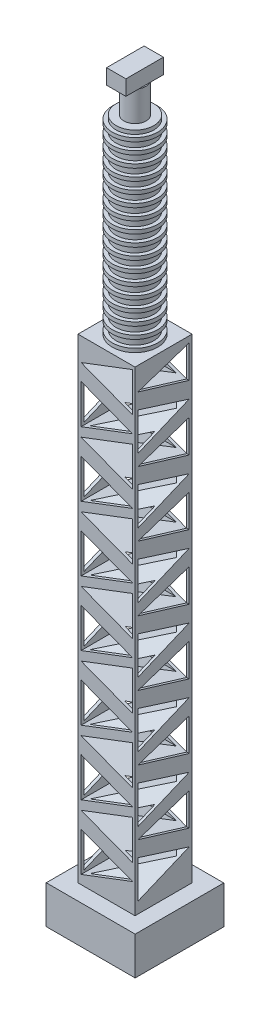
SolidWorks part; units mm, degrees
ref_plane "Alzado" through (0, 0, 0) normal (0, 0, 1) x (1, 0, 0)
ref_plane "Planta" through (0, 0, 0) normal (0, 1, 0) x (1, 0, 0)
ref_plane "Vista lateral" through (0, 0, 0) normal (1, 0, 0) x (0, 0, -1)
sketch "Croquis1" plane through (0, 0, 0) normal (0, 1, 0) x (1, 0, 0)
  line L1 (-150, 150) -> (150, 150)
  line L2 (-150, 150) -> (-150, -150)
  line L3 (-150, -150) -> (150, -150)
  line L4 (150, 150) -> (150, -150)
  line L5 (-150, 150) -> (150, -150) construction
  line L6 (-150, -150) -> (150, 150) construction
  point P0 (0, 0)
  dimension "D1" = 300
  dimension "D2" = 300
extrude "Saliente-Extruir1" add sketch "Croquis1" along normal blind 2500
sketch "Croquis2" plane through (0, 0, 0) normal (0, -1, 0) x (1, 0, 0)
  line L1 (234.0022, -233.0586) -> (-234.0022, -233.0586)
  line L2 (234.0022, -233.0586) -> (234.0022, 233.0586)
  line L3 (234.0022, 233.0586) -> (-234.0022, 233.0586)
  line L4 (-234.0022, -233.0586) -> (-234.0022, 233.0586)
  line L5 (234.0022, -233.0586) -> (-234.0022, 233.0586) construction
  line L6 (234.0022, 233.0586) -> (-234.0022, -233.0586) construction
  point P0 (0, 0)
extrude "Saliente-Extruir2" add sketch "Croquis2" along normal blind 200
sketch "Croquis3" plane through (0, 0, -150) normal (0, 0, -1) x (-1, 0, 0)
  line L0 (-136.8702, 2481.8632) -> (-136.8702, 2275.7806)
  line L1 (-136.8702, 2275.7806) -> (133.7008, 2378.8219)
  line L2 (133.7008, 2378.8219) -> (-136.8702, 2481.8632)
  line L3 (133.7008, 2275.7806) -> (133.7008, 2086.5211)
  line L4 (133.7008, 2086.5211) -> (-136.8702, 2189.5624)
  line L5 (-136.8702, 2189.5624) -> (133.7008, 2292.6037)
  line L6 (133.7008, 2292.6037) -> (133.7008, 2275.7806)
extrude "Cortar-Extruir1" cut sketch "Croquis3" against normal through all
pattern_linear "MatrizL1" count 7 spacing 340 along (0, -1, 0) of "Cortar-Extruir1"
sketch "Croquis4" plane through (-150, 0, 0) normal (-1, 0, 0) x (0, 0, 1)
  line L0 (134.682, 2296.7928) -> (134.682, 2098.5384)
  line L1 (134.682, 2098.5384) -> (-135, 2211.511)
  line L2 (-135, 2211.511) -> (134.682, 2296.7928)
  line L4 (-135, 2468.271) -> (-135, 2296.7928)
  line L5 (-135, 2296.7928) -> (134.682, 2378.8219)
  line L6 (134.682, 2378.8219) -> (-135, 2468.271)
extrude "Cortar-Extruir2" cut sketch "Croquis4" against normal through all
pattern_linear "MatrizL2" count 7 spacing 340 along (0, -1, 0) of "Cortar-Extruir2"
sketch "Croquis5" plane through (0, 2500, 0) normal (0, 1, 0) x (1, 0, 0)
  circle A0 centre (0, 0) radius 99.5107
extrude "Saliente-Extruir3" add sketch "Croquis5" along normal blind 1000
sketch "Croquis6" plane through (0, 2500, 0) normal (0, 1, 0) x (1, 0, 0)
  circle A0 centre (0, 0) radius 119.3429
extrude "Saliente-Extruir4" add sketch "Croquis6" along normal blind 20
pattern_linear "MatrizL4" count 17 spacing 60 along (0, 1, 0) of "Saliente-Extruir4"
sketch "Croquis7" plane through (0, 3500, 0) normal (0, 1, 0) x (1, 0, 0)
  circle A0 centre (0, 0) radius 57.9524
extrude "Saliente-Extruir5" add sketch "Croquis7" along normal blind 158
sketch "Croquis8" plane through (0, 3658, 0) normal (0, 1, 0) x (1, 0, 0)
  line L1 (50.8563, 98.7501) -> (-50.8563, 98.7501)
  line L2 (50.8563, 98.7501) -> (50.8563, -98.7501)
  line L3 (50.8563, -98.7501) -> (-50.8563, -98.7501)
  line L4 (-50.8563, 98.7501) -> (-50.8563, -98.7501)
  line L5 (50.8563, 98.7501) -> (-50.8563, -98.7501) construction
  line L6 (50.8563, -98.7501) -> (-50.8563, 98.7501) construction
  point P0 (0, 0)
extrude "Saliente-Extruir6" add sketch "Croquis8" along normal blind 80
